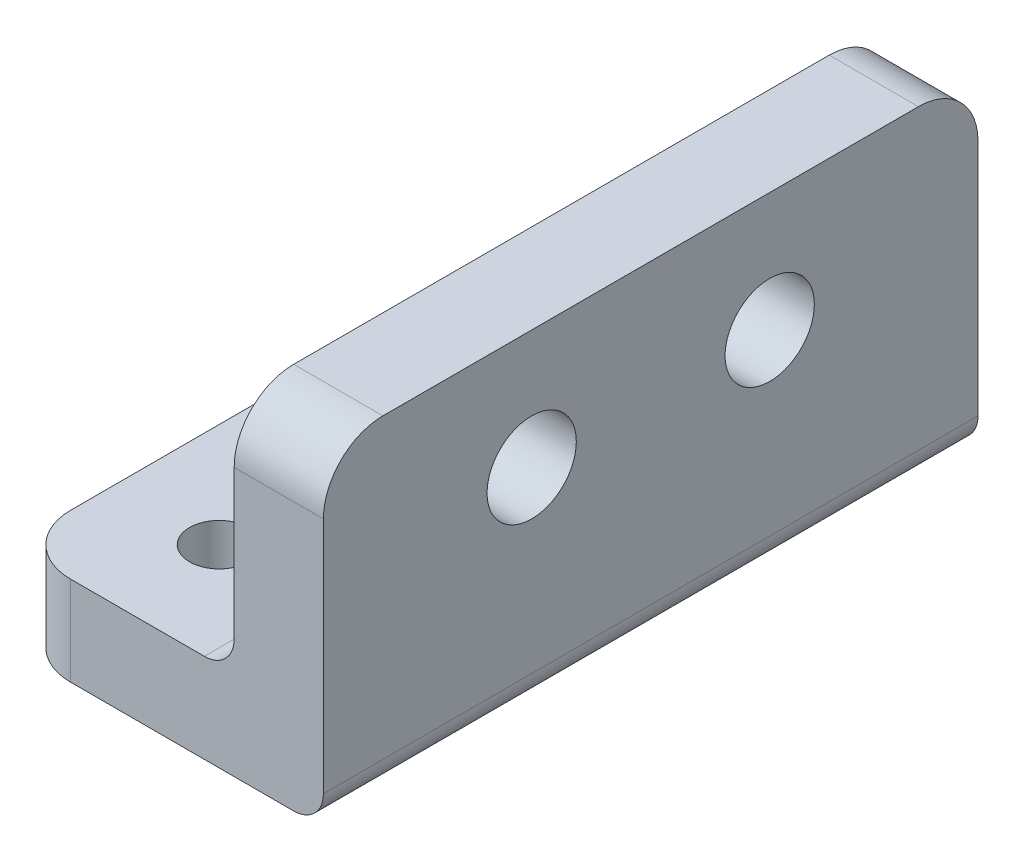
SolidWorks part; units mm, degrees
material "聚脂树脂"
ref_plane "前视基准面" through (0, 0, 0) normal (0, 0, 1) x (1, 0, 0)
ref_plane "上视基准面" through (0, 0, 0) normal (0, 1, 0) x (1, 0, 0)
ref_plane "右视基准面" through (0, 0, 0) normal (1, 0, 0) x (0, 0, -1)
other "Configuration Table"
sketch "草图1" plane through (0, 0, 0) normal (0, 1, 0) x (1, 0, 0)
  line L0 (0, 0) -> (0, 6.1005) construction
  line L1 (-3.5, -11) -> (3.5, -11)
  line L2 (-3.5, -11) -> (-3.5, 11)
  line L3 (-3.5, 11) -> (3.5, 11)
  line L4 (3.5, -11) -> (3.5, 11)
  line L5 (-3.5, -11) -> (3.5, 11) construction
  line L6 (-3.5, 11) -> (3.5, -11) construction
  line L7 (0, 0) -> (7.0113, 0) construction
  line L8 (3.5, 11) -> (7, 11)
  line L9 (7, 11) -> (7, -11)
  line L10 (7, -11) -> (3.5, -11)
  circle A0 centre (0, 7.5) radius 1
  circle A1 centre (0, -7.5) radius 1
  point P0 (0, 0)
  dimension "D1" = 2
  dimension "D2" = 15
  dimension "D3" = 7
  dimension "D4" = 22
  dimension "D5" = 7
extrude "凸台-拉伸1" add sketch "草图1" along normal blind 3 contours L1 L4 L3 L2 A0 A1 | L10 L9 L8 L4
sketch "草图2" plane through (0, 3, 0) normal (0, 1, 0) x (1, 0, 0)
  line L0 (0, 0) -> (16.382, 0) construction
  line L1 (7, 11) -> (4, 11)
  line L2 (-3.5, 11) -> (7, 11) construction
  line L3 (4, 11) -> (4, -11)
  line L4 (-3.5, -11) -> (7, -11) construction
  line L5 (4, -11) -> (7, -11)
  line L6 (7, -11) -> (7, 11)
  dimension "D1" = 3
extrude "凸台-拉伸2" add sketch "草图2" along normal blind 8
sketch "草图3" plane through (4, 0, 0) normal (-1, 0, 0) x (0, 0, 1)
  line L0 (0, 0) -> (0, 14.1124) construction
  line L1 (-11, 11) -> (11, 11) construction
  circle A0 centre (4, 7) radius 1.5
  circle A1 centre (-4, 7) radius 1.5
  dimension "D1" = 3
  dimension "D2" = 8
  dimension "D3" = 4
extrude "切除-拉伸1" cut sketch "草图3" against normal blind 8
fillet "圆角1" radius 2 4 edges at (-3.5, 1.5, 11) (-3.5, 1.5, -11) (5.5, 11, 11) (5.5, 11, -11)
fillet "圆角2" radius 1 2 edges at (4, 3, 0) (7, 0, 0)
